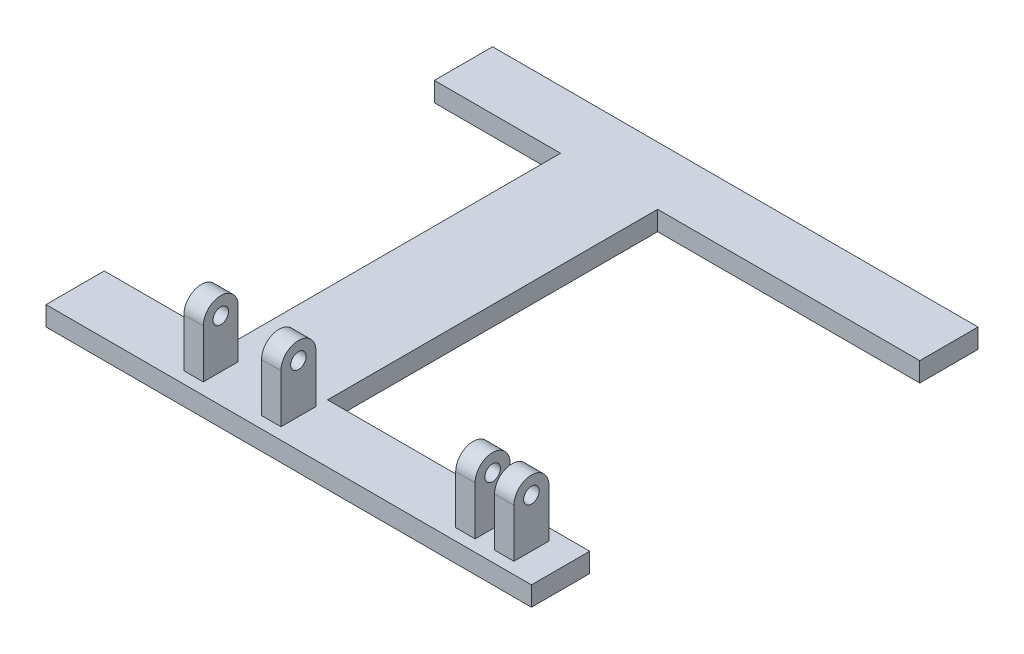
SolidWorks part; units mm, degrees
ref_plane "Front Plane" through (0, 0, 0) normal (0, 0, 1) x (1, 0, 0)
ref_plane "Top Plane" through (0, 0, 0) normal (0, 1, 0) x (1, 0, 0)
ref_plane "Right Plane" through (0, 0, 0) normal (1, 0, 0) x (0, 0, -1)
sketch "Sketch1" plane through (0, 0, 0) normal (0, 1, 0) x (1, 0, 0)
  line L0 (0, 149.4419) -> (0, -200.7311) construction
  line L1 (-125, 90.5492) -> (125, 90.5492)
  line L2 (125, 90.5492) -> (125, 60.5492)
  line L3 (125, 60.5492) -> (-10, 60.5492)
  line L4 (-10, -109.4508) -> (125, -109.4508)
  line L6 (125, -109.4508) -> (125, -139.4508)
  line L7 (125, -139.4508) -> (-125, -139.4508)
  line L8 (-125, -139.4508) -> (-125, -109.4508)
  line L9 (-125, -109.4508) -> (-60, -109.4508)
  line L10 (-10, 60.5492) -> (-10, -109.4508)
  line L11 (-60, 60.5492) -> (-125, 60.5492)
  line L12 (-125, 60.5492) -> (-125, 90.5492)
  line L13 (-60, 60.5492) -> (-60, -109.4508)
  point P17 (125, -124.4508)
  dimension "D1" = 230
  dimension "D2" = 30
  dimension "D3" = 30
  dimension "D4" = 30
  dimension "D6" = 50
  dimension "D7" = 250
  dimension "D8" = 125
  dimension "D9" = 250
  dimension "D10" = 125
extrude "Boss-Extrude1" add sketch "Sketch1" along normal blind 10
ref_plane "Plane1" through (-60, 0, 0) normal (-1, 0, 0) x (0, 0, 1)
sketch "Sketch2" plane through (-60, 0, 0) normal (-1, 0, 0) x (0, 0, 1)
  line L0 (115.4508, 10) -> (133.4508, 10)
  line L1 (109.4508, 10) -> (139.4508, 10) construction
  line L2 (124.4508, 43.1473) -> (124.4508, -9.2162) construction
  line L4 (139.4508, 10) -> (139.4508, 0) construction
  line L6 (115.4508, 35) -> (115.4508, 10)
  line L7 (133.4508, 35) -> (133.4508, 10)
  circle A0 centre (124.4508, 35) radius 4
  arc A3 (133.4508, 35) -> (115.4508, 35) centre (124.4508, 35) ccw
  dimension "D1" = 8
  dimension "D4" = 9
  dimension "D2" = 25
  dimension "D3" = 15
extrude "Boss-Extrude2" add sketch "Sketch2" against normal blind 10
ref_plane "Plane2" through (-20, 0, 0) normal (1, 0, 0) x (0, 0, -1)
pattern_linear "LPattern1" count 2 spacing 40 along (1, 0, 0) of "Boss-Extrude2"
pattern_linear "LPattern2" count 2 spacing 140 along (1, 0, 0) of "Boss-Extrude2"
pattern_linear "LPattern4" count 2 spacing 160 along (1, 0, 0) of "Boss-Extrude2"
